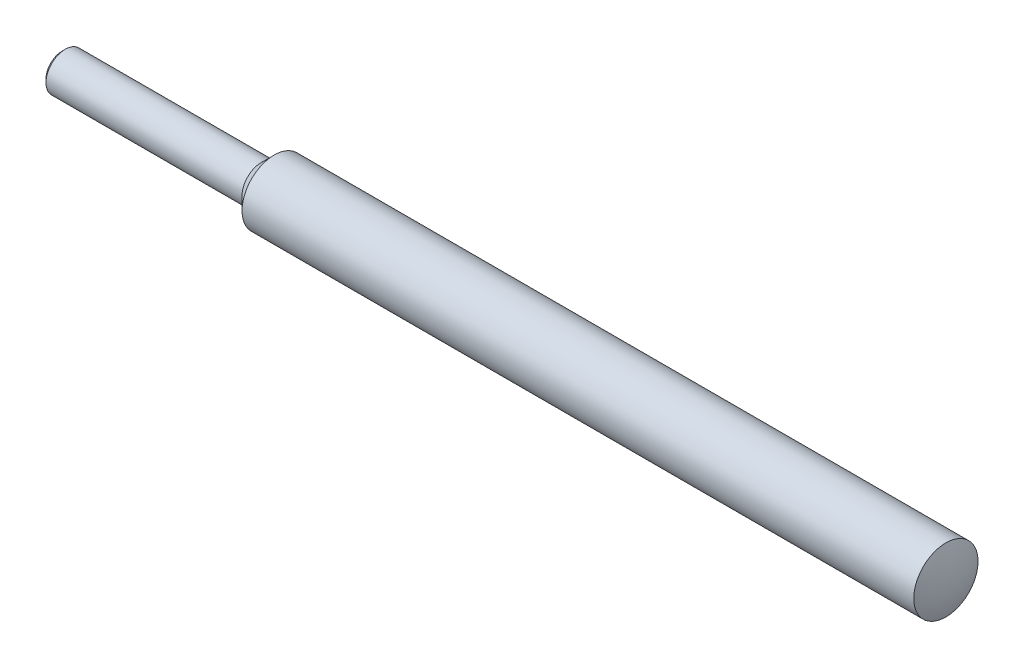
SolidWorks part; units mm, degrees
ref_plane "Front Plane" through (0, 0, 0) normal (0, 0, 1) x (1, 0, 0)
ref_plane "Top Plane" through (0, 0, 0) normal (0, 1, 0) x (1, 0, 0)
ref_plane "Right Plane" through (0, 0, 0) normal (1, 0, 0) x (0, 0, -1)
sketch "Sketch1" plane through (0, 0, 0) normal (0, 0, 1) x (1, 0, 0)
  line L0 (0, 0) -> (287.7916, 0) construction
  line L1 (0, 6) -> (0, 0)
  line L2 (0, 6) -> (62, 6)
  line L3 (62, 6) -> (66, 10)
  line L4 (66, 10) -> (275, 10)
  line L5 (275, 10) -> (275, 0)
  arc A1 (275, 10) -> (277, 0) centre (251, 0) cw
  dimension "D5" = 26
  dimension "D1" = 275
  dimension "D2" = 62
  dimension "D3" = 6
  dimension "D4" = 10
  dimension "D6" = 45
revolve "Revolve1" add sketch "Sketch1" angle 360 about L0
chamfer "Chamfer1" distance 1 angle 45 1 edges at (0, 0, 6)
